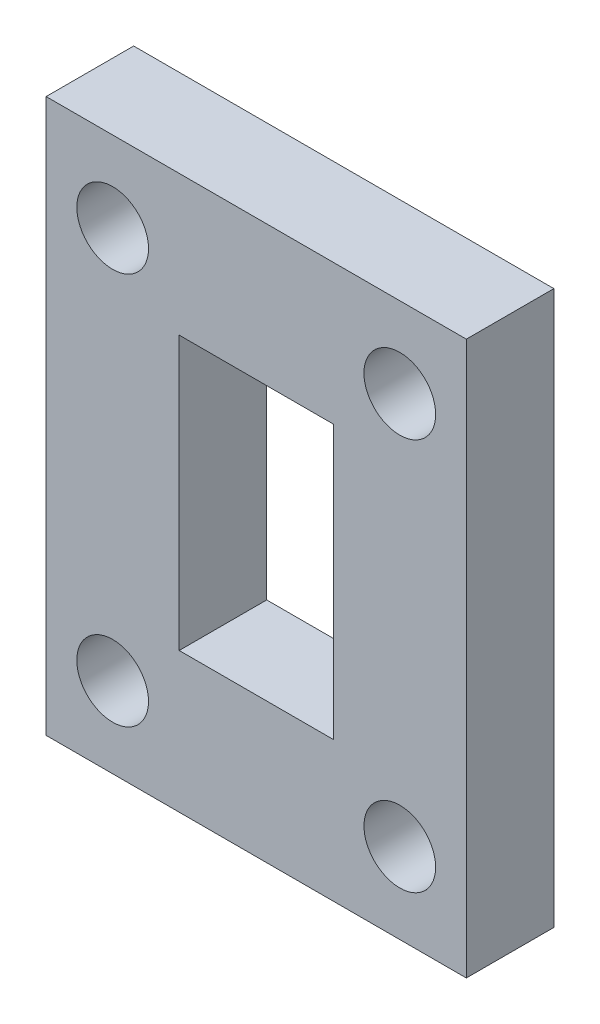
SolidWorks part; units mm, degrees
ref_plane "Front Plane" through (0, 0, 0) normal (0, 0, 1) x (1, 0, 0)
ref_plane "Top Plane" through (0, 0, 0) normal (0, 1, 0) x (1, 0, 0)
ref_plane "Right Plane" through (0, 0, 0) normal (1, 0, 0) x (0, 0, -1)
sketch "Sketch1" plane through (0, 0, 0) normal (0, 0, 1) x (1, 0, 0)
  line L1 (2.794, -4.953) -> (-2.794, -4.953) construction
  line L2 (2.794, -4.953) -> (2.794, 4.953) construction
  line L3 (2.794, 4.953) -> (-2.794, 4.953) construction
  line L4 (-2.794, -4.953) -> (-2.794, 4.953) construction
  line L5 (2.794, -4.953) -> (-2.794, 4.953) construction
  line L6 (2.794, 4.953) -> (-2.794, -4.953) construction
  line L7 (7.62, -10.033) -> (-7.62, -10.033)
  line L8 (7.62, -10.033) -> (7.62, 10.033)
  line L9 (7.62, 10.033) -> (-7.62, 10.033)
  line L10 (-7.62, -10.033) -> (-7.62, 10.033)
  line L11 (7.62, -10.033) -> (-7.62, 10.033) construction
  line L12 (7.62, 10.033) -> (-7.62, -10.033) construction
  line L13 (2.54, -4.699) -> (-2.54, -4.699) construction
  line L14 (2.54, -4.699) -> (2.54, 4.699) construction
  line L15 (2.54, 4.699) -> (-2.54, 4.699) construction
  line L16 (-2.54, -4.699) -> (-2.54, 4.699) construction
  line L17 (2.54, -4.699) -> (-2.54, 4.699) construction
  line L18 (2.54, 4.699) -> (-2.54, -4.699) construction
  line L19 (-2.794, 4.953) -> (2.794, 4.953)
  line L20 (-2.794, 4.953) -> (-2.794, -4.953)
  line L21 (-2.794, -4.953) -> (2.794, -4.953)
  line L22 (2.794, 4.953) -> (2.794, -4.953)
  point P0 (0, 0)
  point P6 (0, 0)
  point P11 (0, 0)
  dimension "D1" = 5.588
  dimension "D2" = 9.906
  dimension "D3" = 5.08
  dimension "D4" = 9.398
  dimension "D5" = 5.08
  dimension "D6" = 5.08
extrude "Boss-Extrude1" add sketch "Sketch1" along normal blind 3.175
sketch "Sketch2" plane through (0, 0, 3.175) normal (0, 0, 1) x (1, 0, 0)
  line L0 (0, 10.033) -> (0, -10.033) construction
  line L1 (7.62, 10.033) -> (-7.62, 10.033) construction
  line L2 (-7.62, -10.033) -> (7.62, -10.033) construction
  line L3 (-7.62, 0) -> (7.62, 0) construction
  line L4 (-7.62, 10.033) -> (-7.62, -10.033) construction
  line L5 (7.62, -10.033) -> (7.62, 10.033) construction
  line L6 (-7.62, 2.794) -> (-2.794, 2.794) construction
  line L7 (-2.794, 4.953) -> (-2.794, -4.953) construction
  circle A0 centre (-5.207, 7.112) radius 1.3
  circle A1 centre (5.207, 7.112) radius 1.3
  circle A2 centre (5.207, -7.112) radius 1.3
  circle A3 centre (-5.207, -7.112) radius 1.3
  point P25 (-5.207, 2.794)
  point P26 (0, 0)
  point P27 (-5.207, 7.1719)
  dimension "D1" = 2.6
  dimension "D2" = 4.318
  dimension "D3" = 7.112
extrude "Cut-Extrude1" cut sketch "Sketch2" against normal up to next
equation "\"t\"=0.125"
equation "\"D1@Boss-Extrude1\"=\"t\""
